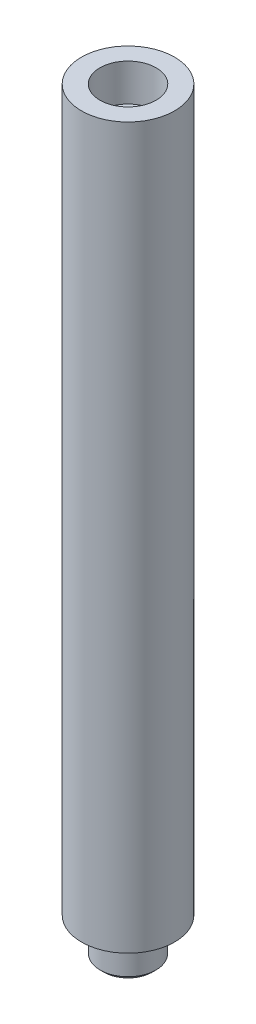
SolidWorks part; units mm, degrees
ref_plane "Front Plane" through (0, 0, 0) normal (0, 0, 1) x (1, 0, 0)
ref_plane "Top Plane" through (0, 0, 0) normal (0, 1, 0) x (1, 0, 0)
ref_plane "Right Plane" through (0, 0, 0) normal (1, 0, 0) x (0, 0, -1)
sketch "Sketch1" plane through (0, 0, 0) normal (0, 0, 1) x (1, 0, 0)
  line L0 (4, 0) -> (4, 193.2)
  line L1 (7.55, 203.2) -> (12.5, 203.2)
  line L2 (12.5, 203.2) -> (12.5, 10)
  line L3 (12.5, 10) -> (7.5, 10)
  line L4 (7.5, 10) -> (7.5, 0)
  line L5 (7.5, 0) -> (4, 0)
  line L6 (0, 0) -> (0, 184.3854) construction
  line L7 (0, 0) -> (-9.8627, 0) construction
  line L8 (7.55, 203.2) -> (7.55, 193.2)
  line L9 (7.55, 193.2) -> (4, 193.2)
  dimension "D1" = 15
  dimension "D2" = 203.2
  dimension "D3" = 25
  dimension "D4" = 10
  dimension "D5" = 8
  dimension "D6" = 15.1
  dimension "D7" = 10
revolve "Revolve1" add sketch "Sketch1" angle 360 about L6
chamfer "Chamfer1" distance 1 angle 45 1 edges at (0, 193.2, -4)
chamfer "Chamfer2" distance 1 angle 45 1 edges at (0, 0, -7.5)
